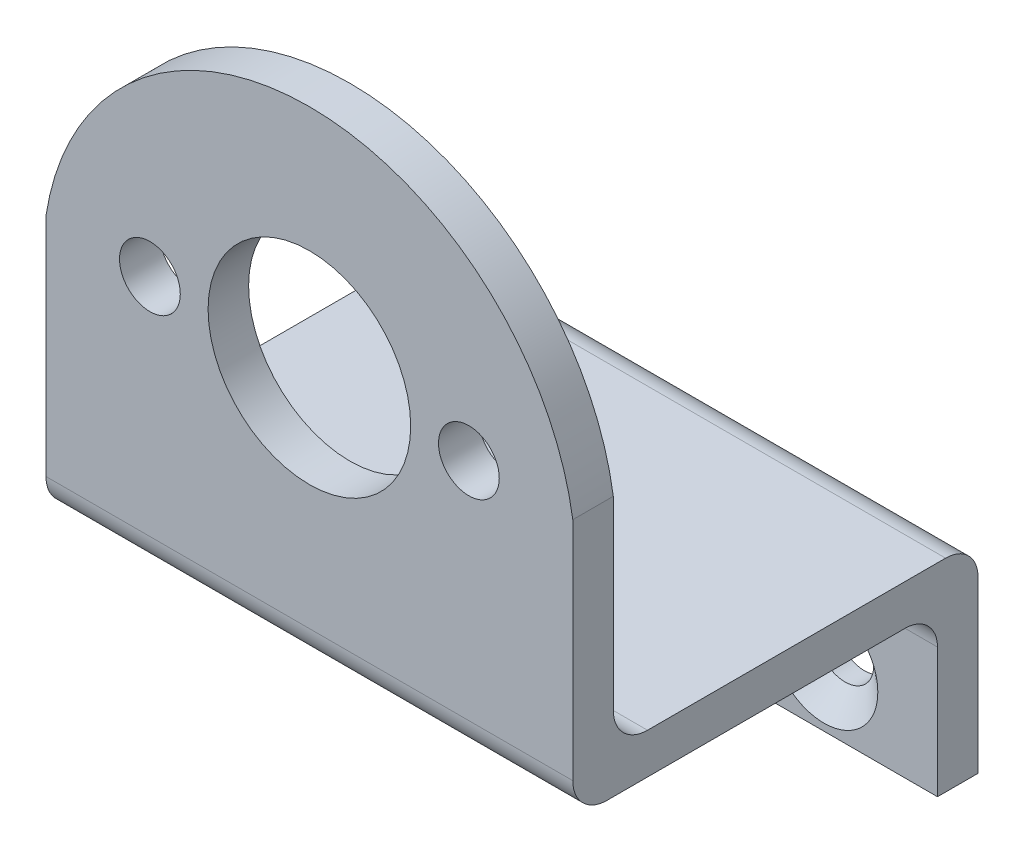
SolidWorks part; units mm, degrees
ref_plane "Front Plane" through (0, 0, 0) normal (0, 0, 1) x (1, 0, 0)
ref_plane "Top Plane" through (0, 0, 0) normal (0, 1, 0) x (1, 0, 0)
ref_plane "Right Plane" through (0, 0, 0) normal (1, 0, 0) x (0, 0, -1)
sketch "Sketch1" plane through (0, 0, 0) normal (1, 0, 0) x (0, 0, -1)
  line L0 (0, 42.0944) -> (0, 9.8503)
  line L1 (2.681, 7.1694) -> (26.035, 7.1694)
  line L3 (0, 42.0944) -> (-3.175, 42.0944)
  line L4 (-3.175, 42.0944) -> (-3.175, 6.6753)
  line L5 (-0.494, 3.9944) -> (22.86, 3.9944)
  line L8 (28.575, 4.6294) -> (28.575, -8.7056)
  line L9 (28.575, -8.7056) -> (25.4, -8.7056)
  line L10 (25.4, -8.7056) -> (25.4, 1.4544)
  arc A2 (-3.175, 6.6753) -> (-0.494, 3.9944) centre (-0.494, 6.6753) ccw
  arc A3 (0, 9.8503) -> (2.681, 7.1694) centre (2.681, 9.8503) ccw
  arc A4 (26.035, 7.1694) -> (28.575, 4.6294) centre (26.035, 4.6294) cw
  arc A5 (22.86, 3.9944) -> (25.4, 1.4544) centre (22.86, 1.4544) cw
  point P14 (26.9875, -8.7056)
  dimension "D2" = 2.54
  dimension "D1" = 3.175
  dimension "D3" = 3.175
  dimension "D4" = 12.7
  dimension "D5" = 38.1
  dimension "D6" = 31.75
  dimension "D7" = 3.175
extrude "Boss-Extrude1" add sketch "Sketch1" along normal blind 41.275 contours L0 A3 L1 A4 L8 L9 L10 A5 L5 A2 L4 L3
sketch "Sketch3" plane through (0, 0, 3.175) normal (0, 0, 1) x (1, 0, 0)
  line L0 (0, 42.0944) -> (41.275, 6.6753) construction
  line L1 (41.275, 7.1694) -> (0, 7.1694) construction
  circle A0 centre (20.6375, 24.3849) radius 17.2155 construction
  circle A1 centre (20.6375, 24.3849) radius 7.9375
extrude "Cut-Extrude2" cut sketch "Sketch3" against normal blind 6.35
sketch "Sketch4" plane through (0, 0, 3.175) normal (0, 0, 1) x (1, 0, 0)
  line L0 (12.7, 24.3849) -> (28.575, 24.3849) construction
  line L1 (41.275, 42.0944) -> (0, 42.0944) construction
  line L2 (0, 42.0944) -> (0, 6.6753) construction
  line L3 (41.275, 42.0944) -> (41.275, 6.6753) construction
  line L4 (0, 24.3849) -> (0, 42.0944)
  line L5 (0, 42.0944) -> (41.275, 42.0944)
  line L6 (41.275, 42.0944) -> (41.275, 24.3849)
  circle A0 centre (33.1341, 24.3144) radius 2.3812
  circle A1 centre (8.1405, 24.3144) radius 2.3813
  circle A2 centre (20.6375, 24.3849) radius 7.9375 construction
  arc A3 (0, 24.3849) -> (41.275, 24.3849) centre (20.6375, 21.2148) cw
  point P12 (20.6375, 24.3849)
  line M6 (0, 42.0944) -> (0, 6.6753)
  line M8 (41.275, 6.6753) -> (41.275, 42.0944)
  line M9 (41.275, 42.0944) -> (0, 42.0944)
  dimension "D2" = 4.7625
  dimension "D1" = 17.78
  dimension "D3" = 24.9936
  dimension "D4" = 12.4968
extrude "Cut-Extrude3" cut sketch "Sketch4" against normal through all contours A3 L5 M6 | A3 M9 M8 | A1 | A0
hole_wizard "CSK for #8 Flat Head Machine Screw (100)2" positions "Sketch9" profile "Sketch10" countersink size "#8" standard "ANSI Inch" end condition through all
sketch "Sketch9" plane through (0, 0, -25.4) normal (0, 0, 1) x (1, 0, 0)
  line L0 (41.275, -8.7056) -> (0, -8.7056) construction
  point P0 (8.89, -3.9431)
  point P2 (32.385, -3.9431)
  point P7 (20.6375, -8.7056)
  dimension "D2" = 4.7625
  dimension "D1" = 23.495
  dimension "D3" = 11.7475
sketch "Sketch10" plane through (8.89, -3.9431, -25.4) normal (1, 0, 0) x (0, -1, 0)
  line L0 (0, 0) -> (0, 3.175)
  line L1 (0, 3.175) -> (2.2479, 3.175)
  line L2 (2.2479, 3.175) -> (2.2479, 1.6518)
  line L3 (2.2479, 1.6518) -> (4.2164, 0)
  line L5 (4.2164, 0) -> (0, 0)
  line L6 (-2.2479, 1.6518) -> (-4.2164, 0) construction
  line L11 (0, -6.35) -> (0, 107.95) construction
  dimension "Thru Hole Dia." = 4.4958
  dimension "Thru Hole Depth" = 3.175
  dimension "Near C'Sink Dia." = 8.4328
  dimension "Near C'Sink Angle" = 100
equation "\"D3@Sketch1\"=\"D1@Sketch1\""
equation "\"D7@Sketch1\"=\"D1@Sketch1\""
equation "\"D4@Sketch4\"=\"D3@Sketch4\"/2"
equation "\"D3@Sketch9\"=\"D1@Sketch9\"/2"
